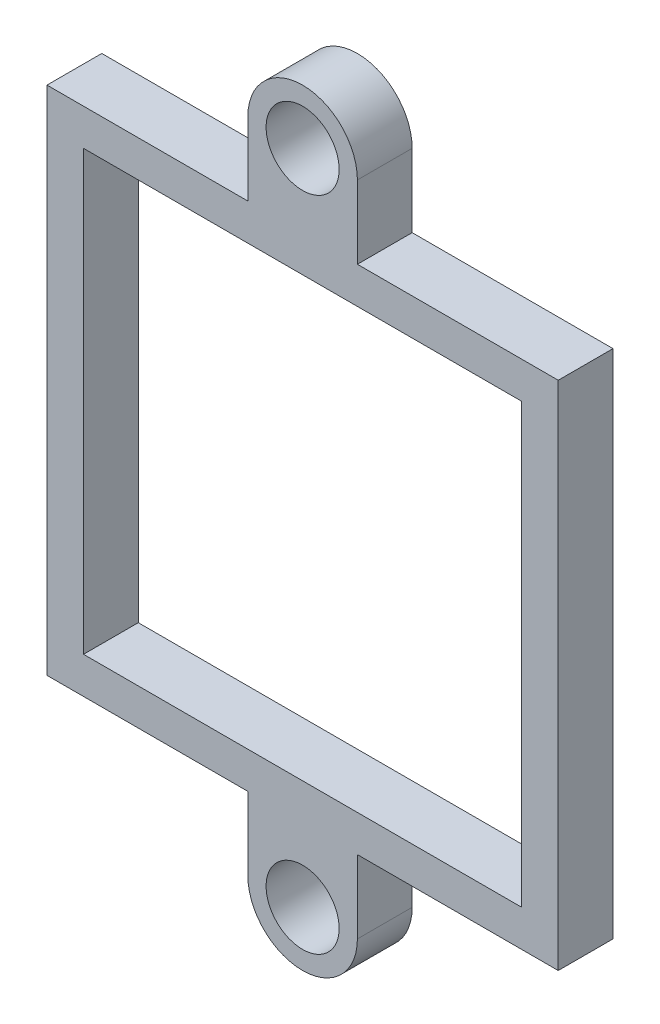
SolidWorks part; units mm, degrees
ref_plane "前视基准面" through (0, 0, 0) normal (0, 0, 1) x (1, 0, 0)
ref_plane "上视基准面" through (0, 0, 0) normal (0, 1, 0) x (1, 0, 0)
ref_plane "右视基准面" through (0, 0, 0) normal (1, 0, 0) x (0, 0, -1)
sketch "草图6" plane through (0, 0, 0) normal (0, 0, 1) x (1, 0, 0)
  line L0 (-7, 7) -> (7, 7)
  line L1 (-6, -6) -> (6, -6)
  line L2 (-6, -6) -> (-6, 6)
  line L3 (-6, 6) -> (6, 6)
  line L4 (6, -6) -> (6, 6)
  line L5 (-6, -6) -> (6, 6) construction
  line L6 (-6, 6) -> (6, -6) construction
  line L7 (7, -7) -> (7, 7)
  line L8 (-7, -7) -> (7, -7)
  line L9 (-7, -7) -> (-7, 7)
  point P0 (0, 0)
  dimension "D1" = 12
  dimension "D3" = 12
  dimension "D2" = 1
extrude "凸台-拉伸3" add sketch "草图6" along normal blind 1.5
sketch "草图7" plane through (0, -7, 0) normal (0, -1, 0) x (1, 0, 0)
  line L0 (-7, 1.5) -> (7, 1.5) construction
  line L1 (-1.5, 0) -> (1.5, 0)
  line L2 (-1.5, 0) -> (-1.5, 1.5)
  line L3 (-1.5, 1.5) -> (1.5, 1.5)
  line L4 (1.5, 0) -> (1.5, 1.5)
  line L5 (-1.5, 0) -> (1.5, 1.5) construction
  line L6 (-1.5, 1.5) -> (1.5, 0) construction
  line L7 (-7, 0) -> (7, 0) construction
  point P0 (0, 0.75)
  dimension "D1" = 3
extrude "凸台-拉伸4" add sketch "草图7" along normal blind 3.5
sketch "草图8" plane through (0, 0, 1.5) normal (0, 0, 1) x (1, 0, 0)
  line L0 (1.5, -10.5) -> (1.5, -7) construction
  line L3 (1.5, -10.5) -> (-1.5, -10.5) construction
  line L4 (-1.5, -10.5) -> (-1.5, -7) construction
  line L5 (1.5, -9) -> (1.5, -10.5)
  line L6 (1.5, -10.5) -> (-1.5, -10.5)
  line L7 (-1.5, -10.5) -> (-1.5, -9)
  circle A0 centre (0, -9) radius 1.5
  line M4 (-1.5, -7) -> (-1.5, -10.5)
  line M5 (-1.5, -10.5) -> (1.5, -10.5)
  line M6 (1.5, -10.5) -> (1.5, -7)
extrude "切除-拉伸3" cut sketch "草图8" against normal blind 4 contours A0 M4 M5 | A0 L6 M6
sketch "草图11" plane through (0, 0, 1.5) normal (0, 0, 1) x (1, 0, 0)
  circle A0 centre (0, -9) radius 1
  dimension "D1" = 9
extrude "切除-拉伸5" cut sketch "草图11" against normal blind 4
mirror "镜向1" about plane through (0, 0, 0) normal (0, 1, 0) of "切除-拉伸3", "凸台-拉伸4", "切除-拉伸5"
